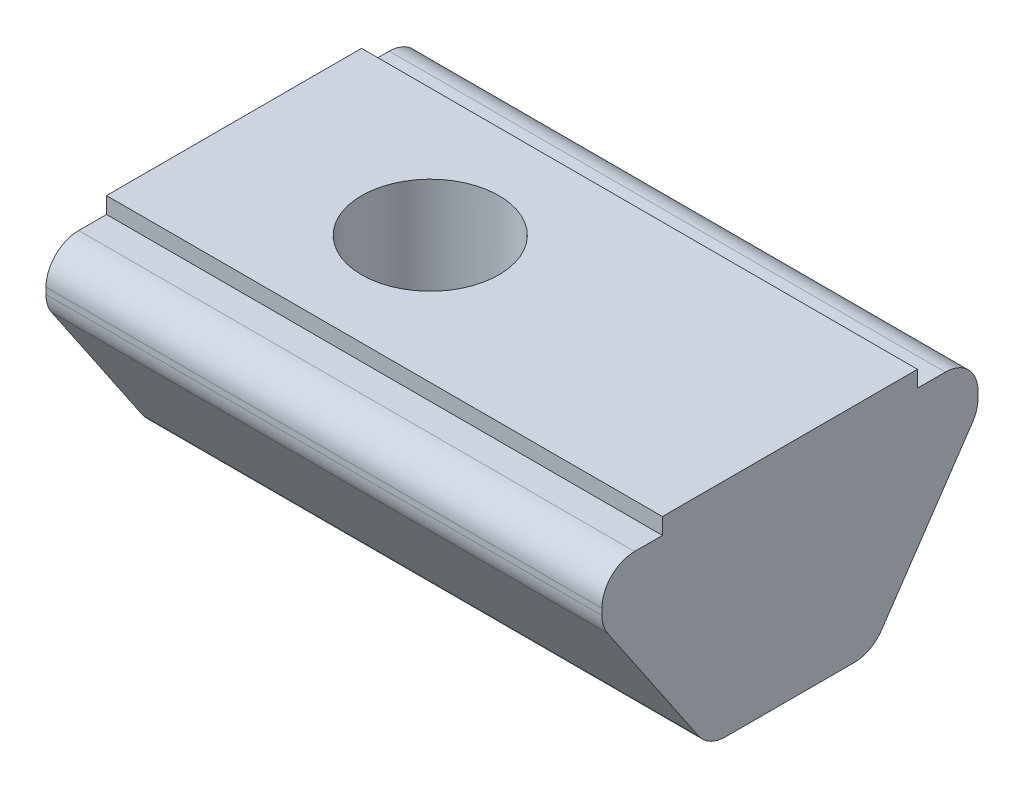
SolidWorks part; units mm, degrees
ref_plane "Front Plane" through (0, 0, 0) normal (0, 0, 1) x (1, 0, 0)
ref_plane "Top Plane" through (0, 0, 0) normal (0, 1, 0) x (1, 0, 0)
ref_plane "Right Plane" through (0, 0, 0) normal (1, 0, 0) x (0, 0, -1)
ref_plane "Plane1" through (-6, 0, 0) normal (1, 0, 0) x (0, 0, -1)
ref_plane "Plane2" through (7.5, 0, 0) normal (1, 0, 0) x (0, 0, -1)
ref_plane "Plane3" through (-3.1, 0, 0) normal (1, 0, 0) x (0, 0, -1)
sketch "Axis_Line_X" plane through (0, 0, 0) normal (0, 1, 0) x (1, 0, 0)
  line L0 (0, 0) -> (50, 0)
  dimension "FIX_2" = 50
sketch "Axis_Line_Z" plane through (0, 0, 0) normal (0, 1, 0) x (1, 0, 0)
  line L0 (0, 0) -> (0, -50)
  dimension "FIX_3" = 50
sketch "Sketch1" plane through (-6, 0, 0) normal (1, 0, 0) x (0, 0, -1)
  line L0 (3.9, 0) -> (-3.9, 0)
  line L1 (-3.9, 0) -> (-3.9, -0.5)
  line L2 (-3.9, -0.5) -> (-5.75, -0.5)
  line L3 (-5.75, -0.5) -> (-5.75, -2)
  line L4 (-5.75, -2) -> (-2.5, -6.8)
  line L5 (-2.5, -6.8) -> (2.5, -6.8)
  line L6 (2.5, -6.8) -> (5.75, -2)
  line L7 (5.75, -2) -> (5.75, -0.5)
  line L8 (5.75, -0.5) -> (3.9, -0.5)
  line L9 (3.9, -0.5) -> (3.9, 0)
  line L10 (0, 0) -> (0, -6.8) construction
  point P15 (-5.75, -2)
  point P18 (-2.5, -6.8)
  point P24 (5.75, -2)
  dimension "FIX_8" = 6.3
  dimension "FIX_9" = 1.5
  dimension "FIX_4" = 11.5
  dimension "FIX_6" = 7.8
  dimension "FIX_5" = 6.8
  dimension "FIX_7" = 5
extrude "Boss-Extrude1" add sketch "Sketch1" along normal blind 17
fillet "Fillet1" radius 1 6 edges at (2.5, -0.5, 5.75) (2.5, -2, 5.75) (2.5, -6.8, 2.5) (2.5, -6.8, -2.5) (2.5, -2, -5.75) (2.5, -0.5, -5.75)
sketch "Sketch2" plane through (7.5, 0, 0) normal (1, 0, 0) x (0, 0, -1)
  line L0 (0, 1.6655) -> (0, -9.505) construction
  line L2 (0, -6.6) -> (2.35, -6.6)
  line L3 (0, -6.6) -> (0, -6.8)
  line L4 (0, -6.8) -> (2.35, -6.8)
  line L5 (2.35, -6.6) -> (2.35, -6.8)
  dimension "FIX_13" = 0.2
  dimension "FIX_12" = 2.35
  dimension "FIX_11" = 6.8
revolve "Cut-Revolve1" cut sketch "Sketch2" angle 360 about L0
sketch "Sketch3" plane through (7.5, 0, 0) normal (1, 0, 0) x (0, 0, -1)
  line L0 (0, 0) -> (0, -7.8) construction
  line L1 (1.99, -6.6) -> (0, -6.6) construction
  line L2 (1.99, -7.8) -> (0, -7.8) construction
  line L3 (1.99, -6.6) -> (0, -6.6)
  line L4 (0, -6.6) -> (0, -7.8)
  arc A0 (0, -7.8) -> (1.99, -6.6) centre (0, -5.55) ccw
  dimension "FIX_17" = 4.5
  dimension "FIX_15" = 7.8
  dimension "FIX_16" = 6.6
revolve "Revolve1" add sketch "Sketch3" angle 360 about L0
hole_wizard "Tapped Hole1" positions "Sketch5" profile "Sketch4" tap size "M5x0.8" standard "JIS" end condition through all
sketch "Sketch5" plane through (0, 0, 0) normal (0, 1, 0) x (1, 0, 0)
  point P0 (0, 0)
cosmetic thread "Thread1" parameters "NFIX_1"=5
sketch "Sketch4" plane through (0, 0, 0) normal (1, 0, 0) x (0, 0, 1)
  line L0 (0, 0) -> (0, 7.8)
  line L1 (0, 7.8) -> (2.1, 7.8)
  line L2 (2.1, 7.8) -> (2.1, 0)
  line L5 (2.1, 0) -> (0, 0)
  line L11 (0, 0) -> (0, 7.8) construction
  dimension "Thru Tap Drill Dia." = 4.2
  dimension "Thru Tap Drill Depth" = 7.8
sketch "Sketch6" [suppressed] plane through (-3.1, 0, 0) normal (1, 0, 0) x (0, 0, -1)
  line L0 (4.9, -0.4) -> (4.9, -0.5)
  line L1 (4.9, -0.5) -> (5, -0.5)
  line L2 (4.9, -0.4) -> (4.9, -0.5) construction
  arc A0 (5, -0.5) -> (4.9, -0.4) centre (4.9, -0.5) ccw
  dimension "FIX_21" = 0.1
  dimension "FIX_19" = 4.9
  dimension "FIX_20" = 0.5
revolve "Revolve2" [suppressed] add sketch "Sketch6" angle 360 about L2
pattern_linear "LPattern1" [suppressed]
equation "\"SHNTP6\" = if ( \"L1\" = 6 , \"suppressed\" , \"unsuppressed\" )"
